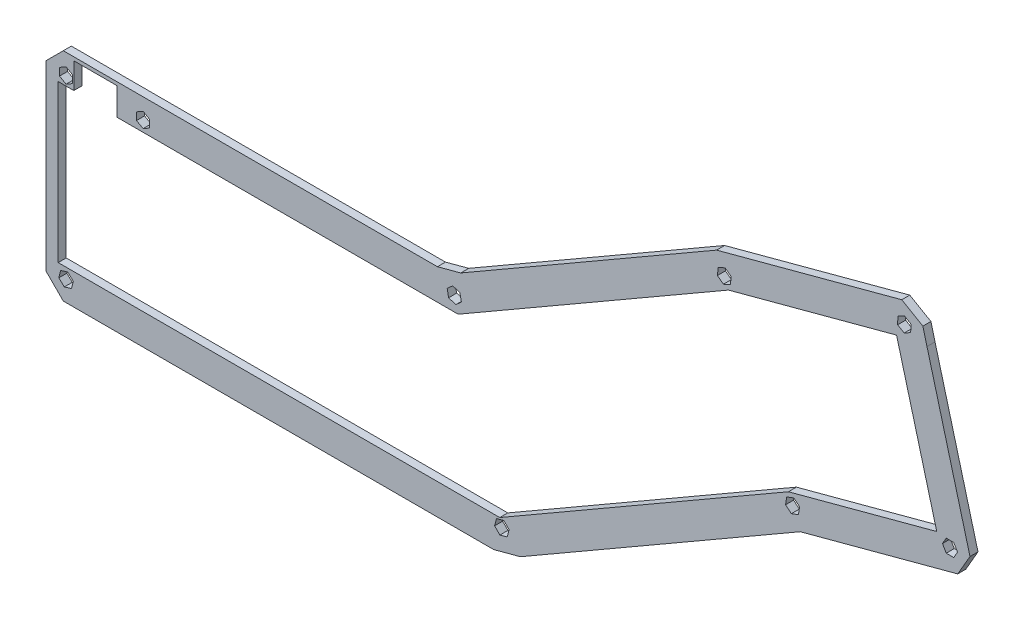
SolidWorks part; units mm, degrees
ref_plane "Plan de face" through (0, 0, 0) normal (0, 0, 1) x (1, 0, 0)
ref_plane "Plan de dessus" through (0, 0, 0) normal (0, 1, 0) x (1, 0, 0)
ref_plane "Plan de droite" through (0, 0, 0) normal (1, 0, 0) x (0, 0, -1)
sketch "Esquisse1" plane through (0, 0, 0) normal (0, 0, 1) x (1, 0, 0)
  line L0 (-73.9886, 18.0851) -> (-59.9886, 18.0851) construction
  line L1 (-73.9886, 37.0851) -> (-59.9886, 37.0851) construction
  line L2 (-73.9886, 37.0851) -> (-73.9886, 23.0851) construction
  line L3 (-73.9886, 23.0851) -> (-59.9886, 23.0851) construction
  line L4 (-59.9886, 37.0851) -> (-59.9886, 23.0851) construction
  line L5 (-73.9886, 18.0851) -> (-73.9886, 4.0851) construction
  line L6 (-73.9886, 4.0851) -> (-59.9886, 4.0851) construction
  line L7 (-59.9886, 18.0851) -> (-59.9886, 4.0851) construction
  line L8 (-73.9886, -0.9149) -> (-59.9886, -0.9149) construction
  line L9 (-73.9886, -0.9149) -> (-73.9886, -14.9149) construction
  line L10 (-73.9886, -14.9149) -> (-59.9886, -14.9149) construction
  line L11 (-59.9886, -0.9149) -> (-59.9886, -14.9149) construction
  line L12 (-73.9886, 37.0851) -> (-73.9886, 18.0851) construction
  line L13 (-54.9886, 18.0851) -> (-40.9886, 18.0851) construction
  line L14 (-54.9886, 37.0851) -> (-40.9886, 37.0851) construction
  line L15 (-54.9886, 37.0851) -> (-54.9886, 23.0851) construction
  line L16 (-54.9886, 23.0851) -> (-40.9886, 23.0851) construction
  line L17 (-40.9886, 37.0851) -> (-40.9886, 23.0851) construction
  line L18 (-54.9886, 18.0851) -> (-54.9886, 4.0851) construction
  line L19 (-54.9886, 4.0851) -> (-40.9886, 4.0851) construction
  line L20 (-40.9886, 18.0851) -> (-40.9886, 4.0851) construction
  line L21 (-54.9886, -0.9149) -> (-40.9886, -0.9149) construction
  line L22 (-54.9886, -0.9149) -> (-54.9886, -14.9149) construction
  line L23 (-54.9886, -14.9149) -> (-40.9886, -14.9149) construction
  line L24 (-40.9886, -0.9149) -> (-40.9886, -14.9149) construction
  line L25 (-54.9886, 37.0851) -> (-54.9886, 18.0851) construction
  line L26 (-35.9886, 18.0851) -> (-21.9886, 18.0851) construction
  line L27 (-35.9886, 37.0851) -> (-21.9886, 37.0851) construction
  line L28 (-35.9886, 37.0851) -> (-35.9886, 23.0851) construction
  line L29 (-35.9886, 23.0851) -> (-21.9886, 23.0851) construction
  line L30 (-21.9886, 37.0851) -> (-21.9886, 23.0851) construction
  line L31 (-35.9886, 18.0851) -> (-35.9886, 4.0851) construction
  line L32 (-35.9886, 4.0851) -> (-21.9886, 4.0851) construction
  line L33 (-21.9886, 18.0851) -> (-21.9886, 4.0851) construction
  line L34 (-35.9886, -0.9149) -> (-21.9886, -0.9149) construction
  line L35 (-35.9886, -0.9149) -> (-35.9886, -14.9149) construction
  line L36 (-35.9886, -14.9149) -> (-21.9886, -14.9149) construction
  line L37 (-21.9886, -0.9149) -> (-21.9886, -14.9149) construction
  line L38 (-35.9886, 37.0851) -> (-35.9886, 18.0851) construction
  line L39 (-16.9886, 18.0851) -> (-2.9886, 18.0851) construction
  line L40 (-16.9886, 37.0851) -> (-2.9886, 37.0851) construction
  line L41 (-16.9886, 37.0851) -> (-16.9886, 23.0851) construction
  line L42 (-16.9886, 23.0851) -> (-2.9886, 23.0851) construction
  line L43 (-2.9886, 37.0851) -> (-2.9886, 23.0851) construction
  line L44 (-16.9886, 18.0851) -> (-16.9886, 4.0851) construction
  line L45 (-16.9886, 4.0851) -> (-2.9886, 4.0851) construction
  line L46 (-2.9886, 18.0851) -> (-2.9886, 4.0851) construction
  line L47 (-16.9886, -0.9149) -> (-2.9886, -0.9149) construction
  line L48 (-16.9886, -0.9149) -> (-16.9886, -14.9149) construction
  line L49 (-16.9886, -14.9149) -> (-2.9886, -14.9149) construction
  line L50 (-2.9886, -0.9149) -> (-2.9886, -14.9149) construction
  line L51 (-16.9886, 37.0851) -> (-16.9886, 18.0851) construction
  line L52 (2.0114, 18.0851) -> (16.0114, 18.0851) construction
  line L53 (2.0114, 37.0851) -> (16.0114, 37.0851) construction
  line L54 (2.0114, 37.0851) -> (2.0114, 23.0851) construction
  line L55 (2.0114, 23.0851) -> (16.0114, 23.0851) construction
  line L56 (16.0114, 37.0851) -> (16.0114, 23.0851) construction
  line L57 (2.0114, 18.0851) -> (2.0114, 4.0851) construction
  line L58 (2.0114, 4.0851) -> (16.0114, 4.0851) construction
  line L59 (16.0114, 18.0851) -> (16.0114, 4.0851) construction
  line L60 (2.0114, -0.9149) -> (16.0114, -0.9149) construction
  line L61 (2.0114, -0.9149) -> (2.0114, -14.9149) construction
  line L62 (2.0114, -14.9149) -> (16.0114, -14.9149) construction
  line L63 (16.0114, -0.9149) -> (16.0114, -14.9149) construction
  line L64 (2.0114, 37.0851) -> (2.0114, 18.0851) construction
  line L65 (21.0114, 18.0851) -> (35.0114, 18.0851) construction
  line L66 (21.0114, 37.0851) -> (35.0114, 37.0851) construction
  line L67 (21.0114, 37.0851) -> (21.0114, 23.0851) construction
  line L68 (21.0114, 23.0851) -> (35.0114, 23.0851) construction
  line L69 (35.0114, 37.0851) -> (35.0114, 23.0851) construction
  line L70 (21.0114, 18.0851) -> (21.0114, 4.0851) construction
  line L71 (21.0114, 4.0851) -> (35.0114, 4.0851) construction
  line L72 (35.0114, 18.0851) -> (35.0114, 4.0851) construction
  line L73 (21.0114, -0.9149) -> (35.0114, -0.9149) construction
  line L74 (21.0114, -0.9149) -> (21.0114, -14.9149) construction
  line L75 (21.0114, -14.9149) -> (35.0114, -14.9149) construction
  line L76 (35.0114, -0.9149) -> (35.0114, -14.9149) construction
  line L77 (21.0114, 37.0851) -> (21.0114, 18.0851) construction
  line L78 (40.0114, 18.0851) -> (54.0114, 18.0851) construction
  line L79 (40.0114, 37.0851) -> (54.0114, 37.0851) construction
  line L80 (40.0114, 37.0851) -> (40.0114, 23.0851) construction
  line L81 (40.0114, 23.0851) -> (54.0114, 23.0851) construction
  line L82 (54.0114, 37.0851) -> (54.0114, 23.0851) construction
  line L83 (40.0114, 18.0851) -> (40.0114, 4.0851) construction
  line L84 (40.0114, 4.0851) -> (54.0114, 4.0851) construction
  line L85 (54.0114, 18.0851) -> (54.0114, 4.0851) construction
  line L86 (40.0114, -0.9149) -> (54.0114, -0.9149) construction
  line L87 (40.0114, -0.9149) -> (40.0114, -14.9149) construction
  line L88 (40.0114, -14.9149) -> (54.0114, -14.9149) construction
  line L89 (54.0114, -0.9149) -> (54.0114, -14.9149) construction
  line L90 (40.0114, 37.0851) -> (40.0114, 18.0851) construction
  line L91 (-73.9886, 18.0851) -> (-54.9886, 18.0851) construction
  line L92 (56.0114, 20.0851) -> (56.7532, 18.8002) construction
  line L93 (38.0114, 39.0851) -> (56.0114, 39.0851) construction
  line L94 (56.0114, 39.0851) -> (56.0114, 21.0851) construction
  line L95 (38.0114, 21.0851) -> (56.0114, 21.0851) construction
  line L96 (38.0114, 39.0851) -> (38.0114, 21.0851) construction
  line L97 (19.0114, 39.0851) -> (37.0114, 39.0851) construction
  line L98 (37.0114, 39.0851) -> (37.0114, 21.0851) construction
  line L99 (19.0114, 21.0851) -> (37.0114, 21.0851) construction
  line L100 (19.0114, 39.0851) -> (19.0114, 21.0851) construction
  line L101 (79.4363, 55.512) -> (88.4363, 39.9235) construction
  line L102 (88.4363, 39.9235) -> (72.8478, 30.9235) construction
  line L103 (63.8478, 46.512) -> (72.8478, 30.9235) construction
  line L104 (79.4363, 55.512) -> (63.8478, 46.512) construction
  line L105 (62.9818, 46.012) -> (71.9818, 30.4235) construction
  line L106 (71.9818, 30.4235) -> (56.3933, 21.4235) construction
  line L107 (47.3933, 37.012) -> (56.3933, 21.4235) construction
  line L108 (62.9818, 46.012) -> (47.3933, 37.012) construction
  line L109 (164.5845, 60.0309) -> (148.9961, 51.0309) construction
  line L110 (62.2497, 43.2799) -> (71.7497, 26.8254) construction
  line L111 (78.7042, 52.7799) -> (88.2042, 36.3254) construction
  line L112 (95.1587, 62.2799) -> (104.6587, 45.8254) construction
  line L113 (111.6132, 71.7799) -> (121.1132, 55.3254) construction
  line L114 (128.0677, 81.2799) -> (137.5677, 64.8254) construction
  line L115 (144.5221, 90.7799) -> (154.0221, 74.3254) construction
  line L116 (148.9961, 51.0309) -> (157.6657, 36.0146) construction
  line L117 (69.1254, 3.371) -> (76.1254, -8.7534) construction
  line L118 (88.2497, -1.7534) -> (76.1254, -8.7534) construction
  line L119 (81.2497, 10.371) -> (88.2497, -1.7534) construction
  line L120 (81.2497, 10.371) -> (69.1254, 3.371) construction
  line L121 (59.6254, 19.8254) -> (66.6254, 7.7011) construction
  line L122 (78.7497, 14.7011) -> (66.6254, 7.7011) construction
  line L123 (71.7497, 26.8254) -> (78.7497, 14.7011) construction
  line L124 (50.1254, 36.2799) -> (57.1254, 24.1556) construction
  line L125 (69.2497, 31.1556) -> (57.1254, 24.1556) construction
  line L126 (62.2497, 43.2799) -> (69.2497, 31.1556) construction
  line L127 (62.2497, 43.2799) -> (50.1254, 36.2799) construction
  line L128 (71.7497, 26.8254) -> (59.6254, 19.8254) construction
  line L129 (85.5799, 12.871) -> (92.5799, 0.7466) construction
  line L130 (104.7042, 7.7466) -> (92.5799, 0.7466) construction
  line L131 (97.7042, 19.871) -> (104.7042, 7.7466) construction
  line L132 (97.7042, 19.871) -> (85.5799, 12.871) construction
  line L133 (76.0799, 29.3254) -> (83.0799, 17.2011) construction
  line L134 (95.2042, 24.2011) -> (83.0799, 17.2011) construction
  line L135 (88.2042, 36.3254) -> (95.2042, 24.2011) construction
  line L136 (66.5799, 45.7799) -> (73.5799, 33.6556) construction
  line L137 (85.7042, 40.6556) -> (73.5799, 33.6556) construction
  line L138 (78.7042, 52.7799) -> (85.7042, 40.6556) construction
  line L139 (78.7042, 52.7799) -> (66.5799, 45.7799) construction
  line L140 (88.2042, 36.3254) -> (76.0799, 29.3254) construction
  line L141 (102.0343, 22.371) -> (109.0343, 10.2466) construction
  line L142 (121.1587, 17.2466) -> (109.0343, 10.2466) construction
  line L143 (114.1587, 29.371) -> (121.1587, 17.2466) construction
  line L144 (114.1587, 29.371) -> (102.0343, 22.371) construction
  line L145 (92.5343, 38.8254) -> (99.5343, 26.7011) construction
  line L146 (111.6587, 33.7011) -> (99.5343, 26.7011) construction
  line L147 (104.6587, 45.8254) -> (111.6587, 33.7011) construction
  line L148 (83.0343, 55.2799) -> (90.0343, 43.1556) construction
  line L149 (102.1587, 50.1556) -> (90.0343, 43.1556) construction
  line L150 (95.1587, 62.2799) -> (102.1587, 50.1556) construction
  line L151 (95.1587, 62.2799) -> (83.0343, 55.2799) construction
  line L152 (104.6587, 45.8254) -> (92.5343, 38.8254) construction
  line L153 (118.4888, 31.871) -> (125.4888, 19.7466) construction
  line L154 (137.6132, 26.7466) -> (125.4888, 19.7466) construction
  line L155 (130.6132, 38.871) -> (137.6132, 26.7466) construction
  line L156 (130.6132, 38.871) -> (118.4888, 31.871) construction
  line L157 (108.9888, 48.3254) -> (115.9888, 36.2011) construction
  line L158 (128.1132, 43.2011) -> (115.9888, 36.2011) construction
  line L159 (121.1132, 55.3254) -> (128.1132, 43.2011) construction
  line L160 (99.4888, 64.7799) -> (106.4888, 52.6556) construction
  line L161 (118.6132, 59.6556) -> (106.4888, 52.6556) construction
  line L162 (111.6132, 71.7799) -> (118.6132, 59.6556) construction
  line L163 (111.6132, 71.7799) -> (99.4888, 64.7799) construction
  line L164 (121.1132, 55.3254) -> (108.9888, 48.3254) construction
  line L165 (134.9433, 41.371) -> (141.9433, 29.2466) construction
  line L166 (154.0677, 36.2466) -> (141.9433, 29.2466) construction
  line L167 (147.0677, 48.371) -> (154.0677, 36.2466) construction
  line L168 (147.0677, 48.371) -> (134.9433, 41.371) construction
  line L169 (125.4433, 57.8254) -> (132.4433, 45.7011) construction
  line L170 (144.5677, 52.7011) -> (132.4433, 45.7011) construction
  line L171 (137.5677, 64.8254) -> (144.5677, 52.7011) construction
  line L172 (115.9433, 74.2799) -> (122.9433, 62.1556) construction
  line L173 (135.0677, 69.1556) -> (122.9433, 62.1556) construction
  line L174 (128.0677, 81.2799) -> (135.0677, 69.1556) construction
  line L175 (128.0677, 81.2799) -> (115.9433, 74.2799) construction
  line L176 (137.5677, 64.8254) -> (125.4433, 57.8254) construction
  line L177 (151.7281, 50.2988) -> (158.3978, 38.7466) construction
  line L178 (170.5221, 45.7466) -> (158.3978, 38.7466) construction
  line L179 (163.8525, 57.2988) -> (170.5221, 45.7466) construction
  line L180 (163.8525, 57.2988) -> (151.7281, 50.2988) construction
  line L181 (141.8978, 67.3254) -> (148.8978, 55.2011) construction
  line L182 (161.0221, 62.2011) -> (148.8978, 55.2011) construction
  line L183 (154.0221, 74.3254) -> (161.0221, 62.2011) construction
  line L184 (132.3978, 83.7799) -> (139.3978, 71.6556) construction
  line L185 (151.5221, 78.6556) -> (139.3978, 71.6556) construction
  line L186 (144.5221, 90.7799) -> (151.5221, 78.6556) construction
  line L187 (144.5221, 90.7799) -> (132.3978, 83.7799) construction
  line L188 (154.0221, 74.3254) -> (141.8978, 67.3254) construction
  line L189 (173.2542, 45.0146) -> (157.6657, 36.0146) construction
  line L190 (164.5845, 60.0309) -> (173.2542, 45.0146) construction
  line L191 (178.3169, 34.0986) -> (169.0534, 56.4627) construction
  line L192 (169.6903, 62.1458) -> (174.1781, 45.3972) construction
  line L193 (174.1781, 45.3972) -> (191.5647, 50.056) construction
  line L194 (187.077, 66.8045) -> (191.5647, 50.056) construction
  line L195 (162.1337, 98.0749) -> (167.0513, 79.7223) construction
  line L196 (169.6903, 62.1458) -> (187.077, 66.8045) construction
  line L197 (167.0513, 79.7223) -> (180.5742, 83.3457) construction
  line L198 (162.1337, 98.0749) -> (175.6567, 101.6983) construction
  line L199 (162.1337, 98.0749) -> (165.7572, 84.5519) construction
  line L200 (165.7572, 84.5519) -> (179.2801, 88.1754) construction
  line L201 (175.6567, 101.6983) -> (179.2801, 88.1754) construction
  line L202 (167.0513, 79.7223) -> (170.6747, 66.1993) construction
  line L203 (170.6747, 66.1993) -> (184.1977, 69.8228) construction
  line L204 (180.5742, 83.3457) -> (184.1977, 69.8228) construction
  line L205 (172.1398, 60.7315) -> (185.6628, 64.355) construction
  line L206 (172.1398, 60.7315) -> (175.5923, 47.8467) construction
  line L207 (175.5923, 47.8467) -> (189.1152, 51.4702) construction
  line L208 (185.6628, 64.355) -> (189.1152, 51.4702) construction
  line L209 (185.4038, 84.6398) -> (198.9268, 88.2633) construction
  line L210 (180.4863, 102.9924) -> (194.0092, 106.6159) construction
  line L211 (180.4863, 102.9924) -> (184.1097, 89.4695) construction
  line L212 (184.1097, 89.4695) -> (197.6327, 93.0929) construction
  line L213 (194.0092, 106.6159) -> (197.6327, 93.0929) construction
  line L214 (185.4038, 84.6398) -> (189.0273, 71.1169) construction
  line L215 (189.0273, 71.1169) -> (202.5503, 74.7403) construction
  line L216 (198.9268, 88.2633) -> (202.5503, 74.7403) construction
  line L217 (190.4924, 65.6491) -> (204.0154, 69.2726) construction
  line L218 (190.4924, 65.6491) -> (193.9449, 52.7643) construction
  line L219 (193.9449, 52.7643) -> (207.4678, 56.3878) construction
  line L220 (204.0154, 69.2726) -> (207.4678, 56.3878) construction
  line L221 (188.0429, 67.0633) -> (192.5307, 50.3148) construction
  line L222 (192.5307, 50.3148) -> (209.9173, 54.9735) construction
  line L223 (205.4296, 71.7221) -> (209.9173, 54.9735) construction
  line L224 (180.4863, 102.9924) -> (185.4038, 84.6398) construction
  line L225 (188.0429, 67.0633) -> (205.4296, 71.7221) construction
  line L226 (203.7564, 89.5574) -> (217.2794, 93.1809) construction
  line L227 (198.8389, 107.91) -> (212.3618, 111.5335) construction
  line L228 (198.8389, 107.91) -> (202.4623, 94.387) construction
  line L229 (202.4623, 94.387) -> (215.9853, 98.0105) construction
  line L230 (212.3618, 111.5335) -> (215.9853, 98.0105) construction
  line L231 (203.7564, 89.5574) -> (207.3799, 76.0344) construction
  line L232 (207.3799, 76.0344) -> (220.9029, 79.6579) construction
  line L233 (217.2794, 93.1809) -> (220.9029, 79.6579) construction
  line L234 (208.845, 70.5667) -> (222.368, 74.1901) construction
  line L235 (208.845, 70.5667) -> (212.2975, 57.6819) construction
  line L236 (212.2975, 57.6819) -> (225.8204, 61.3053) construction
  line L237 (222.368, 74.1901) -> (225.8204, 61.3053) construction
  line L238 (206.3955, 71.9809) -> (210.8833, 55.2324) construction
  line L239 (210.8833, 55.2324) -> (228.2699, 59.8911) construction
  line L240 (223.7822, 76.6396) -> (228.2699, 59.8911) construction
  line L241 (198.8389, 107.91) -> (203.7564, 89.5574) construction
  line L242 (206.3955, 71.9809) -> (223.7822, 76.6396) construction
  line L243 (167.0513, 79.7223) -> (185.4038, 84.6398) construction
  line L244 (38.0114, 20.0851) -> (56.0114, 20.0851) construction
  line L245 (56.0114, 20.0851) -> (56.0114, 2.0851) construction
  line L246 (38.0114, 2.0851) -> (56.0114, 2.0851) construction
  line L247 (38.0114, 20.0851) -> (38.0114, 2.0851) construction
  line L248 (72.4818, 29.5575) -> (56.8933, 20.5575) construction
  line L249 (56.8933, 20.5575) -> (65.8933, 4.969) construction
  line L250 (81.4818, 13.969) -> (65.8933, 4.969) construction
  line L251 (72.4818, 29.5575) -> (81.4818, 13.969) construction
  line L252 (56.8933, 20.5575) -> (57.6111, 19.3142) construction
  line L253 (164.6018, 81.1365) -> (169.2605, 63.7498) construction
  line L254 (169.2605, 63.7498) -> (186.6472, 68.4086) construction
  line L255 (181.9884, 85.7952) -> (186.6472, 68.4086) construction
  line L256 (164.6018, 81.1365) -> (181.9884, 85.7952) construction
  line L257 (154.7542, 77.0575) -> (163.7542, 61.469) construction
  line L258 (163.7542, 61.469) -> (148.1657, 52.469) construction
  line L259 (139.1657, 68.0575) -> (148.1657, 52.469) construction
  line L260 (154.7542, 77.0575) -> (139.1657, 68.0575) construction
  line L261 (196.3894, 109.3242) -> (213.776, 113.983) construction
  line L262 (-94.7538, 35.7952) -> (-76.7538, 35.7952) construction
  line L263 (-94.7538, 35.7952) -> (-94.7538, 2.7952) construction
  line L264 (-94.7538, 2.7952) -> (-76.7538, 2.7952) construction
  line L265 (-76.7538, 35.7952) -> (-76.7538, 2.7952) construction
  line L266 (213.776, 113.983) -> (218.4348, 96.5963) construction
  line L267 (201.0481, 91.9375) -> (218.4348, 96.5963) construction
  line L268 (196.3894, 109.3242) -> (201.0481, 91.9375) construction
  line L269 (-75.9886, -16.9149) -> (-57.9886, -16.9149) construction
  line L270 (-57.9886, 1.0851) -> (-57.9886, -16.9149) construction
  line L271 (-75.9886, 1.0851) -> (-57.9886, 1.0851) construction
  line L272 (-75.9886, 1.0851) -> (-75.9886, -16.9149) construction
  line L273 (38.0114, -16.9149) -> (56.0114, -16.9149) construction
  line L274 (56.0114, 1.0851) -> (56.0114, -16.9149) construction
  line L275 (38.0114, 1.0851) -> (56.0114, 1.0851) construction
  line L276 (38.0114, 1.0851) -> (38.0114, -16.9149) construction
  line L277 (-75.9886, 39.0851) -> (-57.9886, 39.0851) construction
  line L278 (-57.9886, 39.0851) -> (-57.9886, 21.0851) construction
  line L279 (-75.9886, 21.0851) -> (-57.9886, 21.0851) construction
  line L280 (-75.9886, 39.0851) -> (-75.9886, 21.0851) construction
  line L281 (145.2542, 93.512) -> (129.6657, 84.512) construction
  line L282 (129.6657, 84.512) -> (138.6657, 68.9235) construction
  line L283 (154.2542, 77.9235) -> (138.6657, 68.9235) construction
  line L284 (145.2542, 93.512) -> (154.2542, 77.9235) construction
  line L285 (223.4353, 116.5711) -> (228.0941, 99.1845) construction
  line L286 (148.2159, 106.7689) -> (211.1879, 123.6422) construction
  line L287 (177.5508, 35.9482) -> (235.6877, 51.5259) construction
  line L288 (177.5508, 35.9482) -> (72.9989, -24.4149) construction
  line L289 (-95.7538, -26.9149) -> (63.6687, -26.9149) construction
  line L290 (-100.7538, 35.7952) -> (-100.7538, -21.9149) construction
  line L291 (-75.9886, 49.0851) -> (43.3046, 49.0851) construction
  line L292 (148.2159, 106.7689) -> (52.6347, 51.5851) construction
  line L293 (-75.9886, 49.0851) -> (-57.9886, 49.0851) construction
  line L294 (140.2542, 102.1722) -> (124.6657, 93.1722) construction
  line L295 (193.8012, 118.9835) -> (211.1879, 123.6422) construction
  line L296 (213.4714, 45.5731) -> (230.8581, 50.2318) construction
  line L297 (38.0114, -26.9149) -> (38.0114, -85.4624) construction
  line L298 (178.2542, 36.3543) -> (162.6657, 27.3543) construction
  line L299 (38.0114, -26.9149) -> (56.0114, -26.9149) construction
  line L300 (-100.7538, 2.7952) -> (-100.7538, -38.0419) construction
  line L301 (-100.7538, 35.7952) -> (-100.7538, 2.7952) construction
  line L302 (-75.9886, 49.0851) -> (-95.7538, 49.0851) construction
  line L303 (-100.7538, 44.0851) -> (-100.7538, 35.7952) construction
  line L304 (211.1879, 123.6422) -> (216.0693, 124.9502) construction
  line L305 (222.1671, 121.4078) -> (223.4353, 116.5711) construction
  line L306 (228.0941, 99.1845) -> (239.2233, 57.6497) construction
  line L307 (216.0693, 124.9502) -> (222.1671, 121.4078) construction
  line L308 (235.6877, 51.5259) -> (239.2233, 57.6497) construction
  line L309 (63.6687, -26.9149) -> (72.9989, -24.4149) construction
  line L310 (52.6347, 51.5851) -> (43.3046, 49.0851) construction
  line L311 (-95.7538, 49.0851) -> (-100.7538, 44.0851) construction
  line L312 (-100.7538, -21.9149) -> (-95.7538, -26.9149) construction
  line L313 (-95.7538, 49.0851) -> (-95.7538, 44.0851) construction
  line L314 (-95.7538, 44.0851) -> (-100.7538, 44.0851) construction
  line L315 (-95.7538, -26.9149) -> (-95.7538, -21.9149) construction
  line L316 (68.3338, -25.6649) -> (67.0397, -20.8353) construction
  line L317 (47.9697, 50.3351) -> (49.2637, 45.5055) construction
  line L318 (177.5508, 35.9482) -> (175.6374, 40.5676) construction
  line L319 (148.2159, 106.7689) -> (150.1293, 102.1495) construction
  line L320 (239.2233, 57.6497) -> (234.4455, 56.3695) construction
  line L321 (216.0693, 124.9502) -> (217.3634, 120.1206) construction
  line L322 (-75.9886, 49.5851) -> (43.2388, 49.5851) construction
  line L323 (52.4417, 52.051) -> (43.2388, 49.5851) construction
  line L324 (148.0229, 107.2348) -> (52.4417, 52.051) construction
  line L325 (148.0229, 107.2348) -> (211.0584, 124.1252) construction
  line L326 (211.0584, 124.1252) -> (216.1407, 125.487) construction
  line L327 (216.1407, 125.487) -> (222.598, 121.7357) construction
  line L328 (222.598, 121.7357) -> (223.9186, 116.6993) construction
  line L329 (223.9186, 116.6993) -> (228.577, 99.3139) construction
  line L330 (228.577, 99.3139) -> (239.7598, 57.579) construction
  line L331 (236.0172, 51.0966) -> (239.7598, 57.579) construction
  line L332 (177.7438, 35.4823) -> (236.0172, 51.0966) construction
  line L333 (177.7438, 35.4823) -> (73.1918, -24.8808) construction
  line L334 (63.7346, -27.4149) -> (73.1918, -24.8808) construction
  line L335 (-95.9609, -27.4149) -> (63.7346, -27.4149) construction
  line L336 (-101.2538, -22.122) -> (-95.9609, -27.4149) construction
  line L337 (-101.2538, 35.7952) -> (-101.2538, -22.122) construction
  line L338 (-101.2538, 44.2922) -> (-101.2538, 35.7952) construction
  line L339 (-95.9609, 49.5851) -> (-101.2538, 44.2922) construction
  line L340 (-75.9886, 49.5851) -> (-76.7538, 49.5851) construction
  line L341 (2.0114, 40.0851) -> (52.7161, 40.0851)
  line L342 (151.6898, 98.3823) -> (50.7161, 40.0851)
  line L343 (-95.7538, 44.0851) -> (-63.3184, 44.0851) construction
  line L344 (-98.6986, -17.9149) -> (66.2572, -17.9149)
  line L345 (174.0769, 44.3349) -> (66.2572, -17.9149)
  line L346 (174.0769, 44.3349) -> (229.4947, 59.184)
  line L347 (214.4832, 115.2077) -> (229.4947, 59.184)
  line L348 (151.6898, 98.3823) -> (214.4832, 115.2077)
  line L349 (225.2657, 74.9666) -> (228.7182, 62.0818) construction
  line L350 (176.3687, 44.949) -> (189.8917, 48.5724) construction
  line L351 (89.7497, -4.3515) -> (77.6254, -11.3515) construction
  line L352 (-54.9886, -17.9149) -> (-40.9886, -17.9149) construction
  line L353 (-92.8618, 49.5851) -> (-76.7538, 49.5851) construction
  line L354 (2.0114, 40.0851) -> (16.0114, 40.0851) construction
  line L355 (77.2042, 55.378) -> (65.0799, 48.378) construction
  line L356 (179.7098, 105.8902) -> (193.2328, 109.5137) construction
  line L357 (2.0114, 40.0851) -> (-76.7538, 40.0851)
  line L358 (-76.7538, 40.0851) -> (-76.7538, 54.5851) construction
  line L359 (-92.8618, 54.5851) -> (-76.7538, 54.5851) construction
  line L360 (-98.6986, 40.6556) -> (-94.8608, 40.6556)
  line L361 (-94.8608, 40.6556) -> (-92.8618, 40.6556)
  line L362 (-94.8608, 49.5851) -> (-95.9609, 49.5851) construction
  line L363 (-66.9886, 37.0851) -> (-66.9886, 49.5851) construction
  line L364 (-75.9886, 49.5851) -> (-95.9609, 49.5851) construction
  line L365 (-92.8618, 40.6556) -> (-92.8618, 54.5851) construction
  line L366 (-76.7538, 39.0851) -> (-97.0101, 39.0851) construction
  line L367 (-76.7538, 39.0851) -> (-76.7538, 1.0851) construction
  line L368 (-76.7538, 1.0851) -> (-97.0101, 1.0851) construction
  line L369 (-97.0101, 39.0851) -> (-97.0101, 1.0851) construction
  line L370 (-92.8618, 49.5851) -> (-94.8608, 49.5851) construction
  line L371 (-98.6986, 40.6556) -> (-98.6986, -17.9149)
  line L372 (-75.9886, 54.5851) -> (-76.7538, 54.5851) construction
  line L373 (-75.9886, 54.5851) -> (42.5805, 54.5851) construction
  line L374 (50.5118, 56.7103) -> (42.5805, 54.5851) construction
  line L375 (146.093, 111.8941) -> (50.5118, 56.7103) construction
  line L376 (146.093, 111.8941) -> (209.7644, 128.9548) construction
  line L377 (209.7644, 128.9548) -> (216.8547, 130.8547) construction
  line L378 (216.8547, 130.8547) -> (226.9072, 125.0148) construction
  line L379 (226.9072, 125.0148) -> (228.7517, 117.9804) construction
  line L380 (228.7517, 117.9804) -> (233.4066, 100.608) construction
  line L381 (233.4066, 100.608) -> (245.1255, 56.8726) construction
  line L382 (239.3118, 46.803) -> (245.1255, 56.8726) construction
  line L383 (179.6737, 30.823) -> (239.3118, 46.803) construction
  line L384 (179.6737, 30.823) -> (75.1218, -29.5401) construction
  line L385 (64.3928, -32.4149) -> (75.1218, -29.5401) construction
  line L386 (-98.0319, -32.4149) -> (64.3928, -32.4149) construction
  line L387 (-106.2538, -24.1931) -> (-98.0319, -32.4149) construction
  line L388 (-106.2538, 35.7952) -> (-106.2538, -24.1931) construction
  line L389 (-106.2538, 46.3633) -> (-106.2538, 35.7952) construction
  line L390 (-98.0319, 54.5851) -> (-106.2538, 46.3633) construction
  line L391 (-94.8608, 54.5851) -> (-98.0319, 54.5851) construction
  line L392 (-92.8618, 54.5851) -> (-94.8608, 54.5851) construction
  line L393 (-92.8618, 50.2988) -> (-76.7538, 50.2988)
  line L394 (-76.7538, 54.5851) -> (-92.8618, 54.5851) construction
  line L395 (-76.7538, 51.5851) -> (-92.8618, 51.5851)
  line L396 (-92.8618, 51.5851) -> (-94.8608, 51.5851)
  line L397 (-94.8608, 51.5851) -> (-96.7893, 51.5851)
  line L398 (-96.7893, 51.5851) -> (-103.2538, 45.1206)
  line L399 (-103.2538, 45.1206) -> (-103.2538, 35.7952)
  line L400 (-103.2538, 35.7952) -> (-103.2538, -22.9504)
  line L401 (-103.2538, -22.9504) -> (-96.7893, -29.4149)
  line L402 (-96.7893, -29.4149) -> (63.9979, -29.4149)
  line L403 (63.9979, -29.4149) -> (73.9638, -26.7445)
  line L404 (178.5158, 33.6186) -> (73.9638, -26.7445)
  line L405 (178.5158, 33.6186) -> (237.335, 49.3791)
  line L406 (237.335, 49.3791) -> (241.9061, 57.2965)
  line L407 (230.5089, 99.8315) -> (241.9061, 57.2965)
  line L408 (225.8519, 117.2117) -> (230.5089, 99.8315)
  line L409 (224.3217, 123.0473) -> (225.8519, 117.2117)
  line L410 (216.4263, 127.634) -> (224.3217, 123.0473)
  line L411 (210.5408, 126.057) -> (216.4263, 127.634)
  line L412 (147.2509, 109.0986) -> (210.5408, 126.057)
  line L413 (147.2509, 109.0986) -> (51.6698, 53.9147)
  line L414 (51.6698, 53.9147) -> (42.9755, 51.5851)
  line L415 (-75.9886, 51.5851) -> (42.9755, 51.5851)
  line L416 (-75.9886, 51.5851) -> (-76.7538, 51.5851)
  line L417 (-76.7538, 48.6361) -> (-76.7538, 40.0851)
  line L418 (-92.8618, 48.6361) -> (-92.8618, 40.6556)
  line L419 (-76.7538, 50.2988) -> (-76.7538, 48.6361)
  line L420 (-92.8618, 50.2988) -> (-92.8618, 48.6361)
  line L421 (-97.4756, -23.6367) -> (-94.032, -20.1931) construction
  line L422 (-93.3188, 42.6793) -> (-93.3188, 45.491)
  line L423 (-93.3188, 45.491) -> (-95.7538, 46.8968)
  line L424 (-95.7538, 46.8968) -> (-98.1888, 45.491)
  line L425 (-98.1888, 45.491) -> (-98.1888, 42.6793)
  line L426 (-98.1888, 42.6793) -> (-95.7538, 41.2734)
  line L427 (-95.7538, 41.2734) -> (-93.3188, 42.6793)
  line L428 (-64.5536, 45.491) -> (-66.9886, 46.8968)
  line L429 (-66.9886, 46.8968) -> (-69.4236, 45.491)
  line L430 (-69.4236, 45.491) -> (-69.4236, 42.6793)
  line L431 (-69.4236, 42.6793) -> (-66.9886, 41.2734)
  line L432 (-66.9886, 41.2734) -> (-64.5536, 42.6793)
  line L433 (-64.5536, 42.6793) -> (-64.5536, 45.491)
  line L434 (51.9317, 44.6181) -> (51.3662, 47.3724)
  line L435 (51.3662, 47.3724) -> (48.6982, 48.2597)
  line L436 (48.6982, 48.2597) -> (46.5957, 46.3928)
  line L437 (46.5957, 46.3928) -> (47.1613, 43.6386)
  line L438 (47.1613, 43.6386) -> (49.8293, 42.7512)
  line L439 (49.8293, 42.7512) -> (51.9317, 44.6181)
  line L440 (152.7035, 103.2806) -> (150.4369, 104.9443)
  line L441 (150.4369, 104.9443) -> (147.8627, 103.8133)
  line L442 (147.8627, 103.8133) -> (147.5551, 101.0185)
  line L443 (147.5551, 101.0185) -> (149.8217, 99.3547)
  line L444 (149.8217, 99.3547) -> (152.3959, 100.4857)
  line L445 (152.3959, 100.4857) -> (152.7035, 103.2806)
  line L446 (219.7717, 118.6694) -> (219.8243, 121.4806)
  line L447 (219.8243, 121.4806) -> (217.416, 122.9318)
  line L448 (217.416, 122.9318) -> (214.9551, 121.5717)
  line L449 (214.9551, 121.5717) -> (214.9025, 118.7605)
  line L450 (214.9025, 118.7605) -> (217.3108, 117.3094)
  line L451 (217.3108, 117.3094) -> (219.7717, 118.6694)
  line L452 (237.2572, 56.3695) -> (235.8513, 58.8045)
  line L453 (235.8513, 58.8045) -> (233.0396, 58.8045)
  line L454 (233.0396, 58.8045) -> (231.6338, 56.3695)
  line L455 (231.6338, 56.3695) -> (233.0396, 53.9345)
  line L456 (233.0396, 53.9345) -> (235.8513, 53.9345)
  line L457 (235.8513, 53.9345) -> (237.2572, 56.3695)
  line L458 (178.2704, 41.554) -> (176.0996, 43.341)
  line L459 (176.0996, 43.341) -> (173.4666, 42.3546)
  line L460 (173.4666, 42.3546) -> (173.0044, 39.5812)
  line L461 (173.0044, 39.5812) -> (175.1751, 37.7942)
  line L462 (175.1751, 37.7942) -> (177.8081, 38.7806)
  line L463 (177.8081, 38.7806) -> (178.2704, 41.554)
  line L464 (69.7556, -20.1075) -> (67.7674, -18.1194)
  line L465 (67.7674, -18.1194) -> (65.0515, -18.8471)
  line L466 (65.0515, -18.8471) -> (64.3238, -21.563)
  line L467 (64.3238, -21.563) -> (66.312, -23.5512)
  line L468 (66.312, -23.5512) -> (69.0279, -22.8234)
  line L469 (69.0279, -22.8234) -> (69.7556, -20.1075)
  line L471 (-93.0572, -21.1185) -> (-95.0952, -19.1814)
  line L472 (-95.0952, -19.1814) -> (-97.7917, -19.9778)
  line L473 (-97.7917, -19.9778) -> (-98.4503, -22.7113)
  line L474 (-98.4503, -22.7113) -> (-96.4124, -24.6484)
  line L475 (-96.4124, -24.6484) -> (-93.7158, -23.852)
  line L476 (-93.7158, -23.852) -> (-93.0572, -21.1185)
  circle A0 centre (-95.7538, 44.0851) radius 1.5 construction
  circle A1 centre (-95.7538, -21.9149) radius 1.5 construction
  circle A2 centre (67.0397, -20.8353) radius 1.5 construction
  circle A3 centre (49.2637, 45.5055) radius 1.5 construction
  circle A4 centre (175.6374, 40.5676) radius 1.5 construction
  circle A5 centre (150.1293, 102.1495) radius 1.5 construction
  circle A6 centre (234.4455, 56.3695) radius 1.5 construction
  circle A7 centre (217.3634, 120.1206) radius 1.5 construction
  circle A8 centre (-66.9886, 44.0851) radius 1.5 construction
  circle A9 centre (-95.7538, 44.0851) radius 2.435 construction
  circle A10 centre (-66.9886, 44.0851) radius 2.435 construction
  circle A11 centre (49.2637, 45.5055) radius 2.435 construction
  circle A12 centre (150.1293, 102.1495) radius 2.435 construction
  circle A13 centre (217.3634, 120.1206) radius 2.435 construction
  circle A14 centre (234.4455, 56.3695) radius 2.435 construction
  circle A15 centre (175.6374, 40.5676) radius 2.435 construction
  circle A16 centre (67.0397, -20.8353) radius 2.435 construction
  circle A17 centre (-95.7538, -21.9149) radius 2.435 construction
  point P304 (48.3046, 49.0851)
  point P305 (240.5174, 52.82)
  point P308 (68.6687, -26.9149)
  point P309 (-100.7538, -26.9149)
  point P311 (-100.7538, 49.0851)
  point P312 (220.8989, 126.2443)
  point P505 (-95.7538, -21.9149)
  dimension "D32" = 3
  dimension "D33" = 5
  dimension "D40" = 5
  dimension "D41" = 5
  dimension "D42" = 5
  dimension "D43" = 5
  dimension "D44" = 0.5
  dimension "D53" = 3
  dimension "D47" = 5
  dimension "D1" = 14
  dimension "D2" = 14
  dimension "D4" = 19
  dimension "D6" = 19
  dimension "D7" = 30
  dimension "D10" = 1
  dimension "D11" = 2
  dimension "D13" = 0.5
  dimension "D15" = 2
  dimension "D12" = 7.5
  dimension "D14" = 19
  dimension "D18" = 2
  dimension "D20" = 18
  dimension "D21" = 33
  dimension "D22" = 2
  dimension "D54" = 4.87
  dimension "D55" = 4.87
  dimension "D56" = 4.87
  dimension "D57" = 4.87
  dimension "D58" = 4.87
  dimension "D59" = 4.87
  dimension "D60" = 4.87
  dimension "D61" = 4.87
  dimension "D62" = 4.87
  dimension "D63" = 4.87
  dimension "D8" = 2
  dimension "D9" = 2
  dimension "D16" = 2
  dimension "D19" = 2
  dimension "D23" = 2
  dimension "D24" = 10
  dimension "D25" = 10
  dimension "D26" = 10
  dimension "D27" = 10
  dimension "D28" = 10
  dimension "D29" = 6
  dimension "D30" = 10
  dimension "D31" = 10
  dimension "D45" = 3
  dimension "D46" = 3
  dimension "D48" = 3
  dimension "D49" = 3
  dimension "D50" = 3
  dimension "D51" = 3
  dimension "D52" = 3
  dimension "D3" = 3
  dimension "D5" = 7
  dimension "D17" = 3
extrude "Boss.-Extru.1" add sketch "Esquisse1" along normal blind 3
